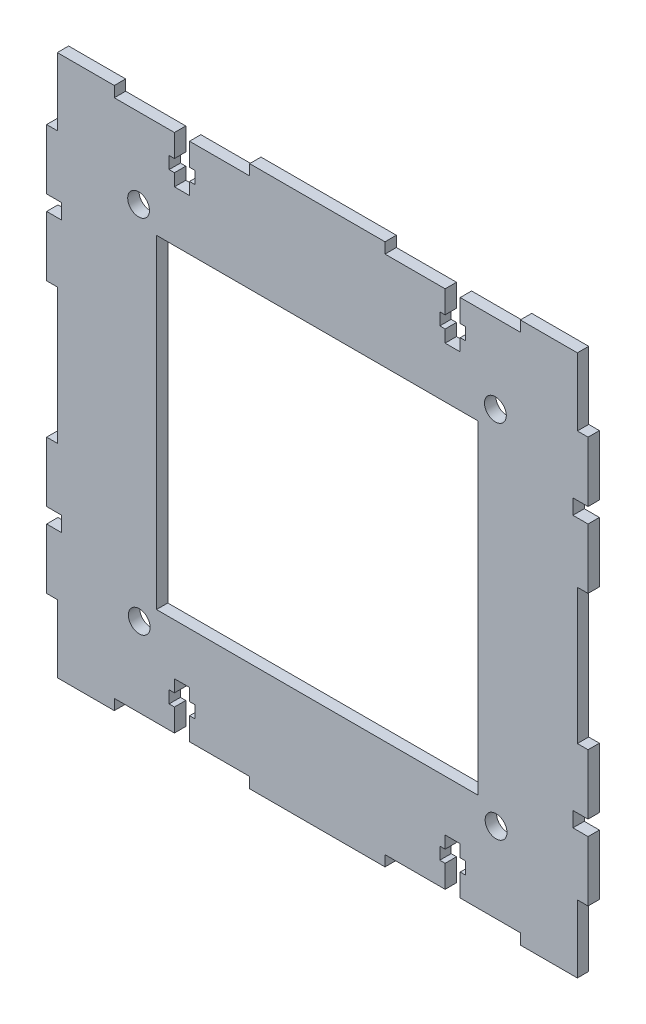
SolidWorks part; units mm, degrees
ref_plane "Front Plane" through (0, 0, 0) normal (0, 0, 1) x (1, 0, 0)
ref_plane "Top Plane" through (0, 0, 0) normal (0, 1, 0) x (1, 0, 0)
ref_plane "Right Plane" through (0, 0, 0) normal (1, 0, 0) x (0, 0, -1)
sketch "Sketch1" plane through (0, 0, 0) normal (0, 0, 1) x (1, 0, 0)
  line L0 (134.3663, 315.8255) -> (134.3663, 296.8984)
  line L1 (134.3663, 296.8984) -> (131.3856, 296.8984)
  line L2 (131.3856, 296.8984) -> (131.3856, 280.0825)
  line L3 (131.3856, 280.0825) -> (135.6082, 280.0825)
  line L4 (135.6082, 280.0825) -> (135.6082, 277.9712)
  line L5 (135.6082, 277.9712) -> (135.6082, 275.86)
  line L6 (135.6082, 275.86) -> (131.3856, 275.86)
  line L7 (131.3856, 275.86) -> (131.3856, 259.0441)
  line L8 (131.3856, 259.0441) -> (134.3663, 259.0441)
  line L9 (134.3663, 259.0441) -> (134.3663, 221.1899)
  line L10 (134.3663, 221.1899) -> (131.3856, 221.1899)
  line L11 (131.3856, 221.1899) -> (131.3856, 204.3741)
  line L12 (131.3856, 204.3741) -> (135.6082, 204.3741)
  line L13 (135.6082, 204.3741) -> (135.6082, 202.2628)
  line L14 (135.6082, 202.2628) -> (135.6082, 200.1515)
  line L15 (135.6082, 200.1515) -> (131.3856, 200.1515)
  line L16 (131.3856, 200.1515) -> (131.3856, 183.3357)
  line L17 (134.3663, 183.3357) -> (134.3663, 164.4086)
  line L18 (134.3663, 164.4086) -> (150.3127, 164.4086)
  line L19 (150.3127, 164.4086) -> (150.3127, 167.3893)
  line L20 (150.3127, 167.3893) -> (167.1286, 167.3893)
  line L21 (167.1286, 167.3893) -> (167.1286, 173.6983)
  line L22 (167.1286, 173.6983) -> (165.6382, 173.6983)
  line L23 (165.6382, 173.6983) -> (165.6382, 177.126)
  line L24 (165.6382, 177.126) -> (167.1286, 177.126)
  line L25 (167.1286, 177.126) -> (167.1286, 180.5538)
  line L26 (167.1286, 180.5538) -> (171.3511, 180.5538)
  line L27 (171.3511, 180.5538) -> (171.3511, 177.126)
  line L28 (171.3511, 177.126) -> (172.8415, 177.126)
  line L29 (172.8415, 177.126) -> (172.8415, 173.6983)
  line L30 (172.8415, 173.6983) -> (171.3511, 173.6983)
  line L31 (171.3511, 173.6983) -> (171.3511, 167.3893)
  line L32 (171.3511, 167.3893) -> (188.167, 167.3893)
  line L33 (188.167, 167.3893) -> (188.167, 164.4086)
  line L34 (188.167, 164.4086) -> (226.0212, 164.4086)
  line L35 (226.0212, 164.4086) -> (226.0212, 167.3893)
  line L36 (226.0212, 167.3893) -> (242.837, 167.3893)
  line L37 (242.837, 167.3893) -> (242.837, 173.6983)
  line L38 (242.837, 173.6983) -> (241.3467, 173.6983)
  line L39 (241.3467, 173.6983) -> (241.3467, 177.126)
  line L40 (241.3467, 177.126) -> (242.837, 177.126)
  line L41 (242.837, 177.126) -> (242.837, 180.5538)
  line L42 (242.837, 180.5538) -> (247.0596, 180.5538)
  line L43 (247.0596, 180.5538) -> (247.0596, 177.126)
  line L44 (247.0596, 177.126) -> (248.5499, 177.126)
  line L45 (248.5499, 177.126) -> (248.5499, 173.6983)
  line L46 (248.5499, 173.6983) -> (247.0596, 173.6983)
  line L47 (247.0596, 173.6983) -> (247.0596, 167.3893)
  line L48 (247.0596, 167.3893) -> (263.8754, 167.3893)
  line L49 (263.8754, 167.3893) -> (263.8754, 164.4086)
  line L50 (263.8754, 164.4086) -> (279.8218, 164.4086)
  line L51 (279.8218, 164.4086) -> (279.8218, 183.3357)
  line L52 (279.8218, 183.3357) -> (282.8025, 183.3357)
  line L53 (282.8025, 183.3357) -> (282.8025, 200.1515)
  line L54 (282.8025, 200.1515) -> (278.5799, 200.1515)
  line L55 (278.5799, 200.1515) -> (278.5799, 202.2628)
  line L56 (278.5799, 202.2628) -> (278.5799, 204.3741)
  line L57 (278.5799, 204.3741) -> (282.8025, 204.3741)
  line L58 (282.8025, 204.3741) -> (282.8025, 221.1899)
  line L59 (282.8025, 221.1899) -> (279.8218, 221.1899)
  line L60 (279.8218, 221.1899) -> (279.8218, 259.0441)
  line L61 (279.8218, 259.0441) -> (282.8025, 259.0441)
  line L62 (282.8025, 259.0441) -> (282.8025, 275.86)
  line L63 (282.8025, 275.86) -> (278.5799, 275.86)
  line L64 (278.5799, 275.86) -> (278.5799, 277.9712)
  line L65 (278.5799, 277.9712) -> (278.5799, 280.0825)
  line L66 (278.5799, 280.0825) -> (282.8025, 280.0825)
  line L67 (282.8025, 280.0825) -> (282.8025, 296.8984)
  line L68 (282.8025, 296.8984) -> (279.8218, 296.8984)
  line L69 (279.8218, 296.8984) -> (279.8218, 315.8255)
  line L70 (279.8218, 315.8255) -> (263.8754, 315.8255)
  line L71 (263.8754, 315.8255) -> (263.8754, 312.8448)
  line L72 (263.8754, 312.8448) -> (247.0596, 312.8448)
  line L73 (247.0596, 312.8448) -> (247.0596, 306.5358)
  line L74 (247.0596, 306.5358) -> (248.5499, 306.5358)
  line L75 (248.5499, 306.5358) -> (248.5499, 303.108)
  line L76 (248.5499, 303.108) -> (247.0596, 303.108)
  line L77 (247.0596, 303.108) -> (247.0596, 299.6803)
  line L78 (247.0596, 299.6803) -> (242.837, 299.6803)
  line L79 (242.837, 299.6803) -> (242.837, 303.108)
  line L80 (242.837, 303.108) -> (241.3467, 303.108)
  line L81 (241.3467, 303.108) -> (241.3467, 306.5358)
  line L82 (241.3467, 306.5358) -> (242.837, 306.5358)
  line L83 (242.837, 306.5358) -> (242.837, 312.8448)
  line L84 (242.837, 312.8448) -> (226.0212, 312.8448)
  line L85 (226.0212, 312.8448) -> (226.0212, 315.8255)
  line L86 (226.0212, 315.8255) -> (188.167, 315.8255)
  line L87 (188.167, 315.8255) -> (188.167, 312.8448)
  line L88 (188.167, 312.8448) -> (171.3511, 312.8448)
  line L89 (171.3511, 312.8448) -> (171.3511, 306.5358)
  line L90 (171.3511, 306.5358) -> (172.8415, 306.5358)
  line L91 (172.8415, 306.5358) -> (172.8415, 303.108)
  line L92 (172.8415, 303.108) -> (171.3511, 303.108)
  line L93 (171.3511, 303.108) -> (171.3511, 299.6803)
  line L94 (171.3511, 299.6803) -> (167.1286, 299.6803)
  line L95 (167.1286, 299.6803) -> (167.1286, 303.108)
  line L96 (167.1286, 303.108) -> (165.6382, 303.108)
  line L97 (165.6382, 303.108) -> (165.6382, 306.5358)
  line L98 (165.6382, 306.5358) -> (167.1286, 306.5358)
  line L99 (167.1286, 306.5358) -> (167.1286, 312.8448)
  line L100 (167.1286, 312.8448) -> (150.3127, 312.8448)
  line L101 (150.3127, 312.8448) -> (150.3127, 315.8255)
  line L102 (150.3127, 315.8255) -> (134.3663, 315.8255)
  line L103 (134.3663, 240.117) -> (279.8218, 240.117) construction
  line L104 (207.0941, 315.8255) -> (207.0941, 164.4086) construction
  line L109 (131.3856, 183.3357) -> (134.3663, 183.3357)
  line L110 (162.1075, 285.4402) -> (162.1075, 194.7939)
  line L111 (162.1075, 194.7939) -> (252.0806, 194.7939)
  line L112 (252.0806, 285.4402) -> (252.0806, 194.7939)
  line L113 (162.1075, 285.4402) -> (252.0806, 285.4402)
  circle A24 centre (157.1075, 290.442) radius 3.05
  circle A25 centre (256.8931, 290.6858) radius 3.05
  circle A26 centre (257.0806, 189.7958) radius 3.05
  circle A27 centre (157.2953, 189.5483) radius 3.05
extrude "Boss-Extrude1" add sketch "Sketch1" along normal blind 3.175
